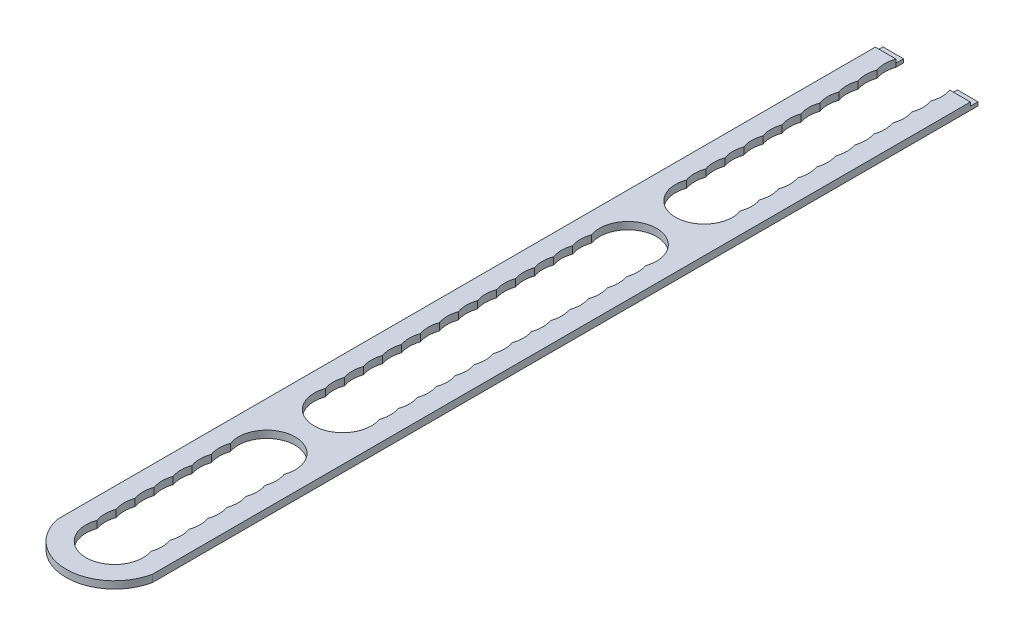
SolidWorks part; units mm, degrees
ref_plane "Front Plane" through (0, 0, 0) normal (0, 0, 1) x (1, 0, 0)
ref_plane "Top Plane" through (0, 0, 0) normal (0, 1, 0) x (1, 0, 0)
ref_plane "Right Plane" through (0, 0, 0) normal (1, 0, 0) x (0, 0, -1)
sketch "Sketch6" plane through (0, 0, 0) normal (0, 1, 0) x (1, 0, 0)
  line L0 (0, 195) -> (0, -195) construction
  line L1 (-12.5, -195) -> (12.5, -195)
  line L2 (-12.5, -195) -> (-12.5, 195)
  line L3 (-12.5, 195) -> (12.5, 195)
  line L4 (12.5, -195) -> (12.5, 195)
  line L5 (-12.5, -195) -> (12.5, 195) construction
  line L6 (-12.5, 195) -> (12.5, -195) construction
  line L7 (-12.5, 22.5) -> (12.5, 22.5)
  line L8 (-12.5, -46.875) -> (12.5, -46.875) construction
  line L9 (-12.5, -140.625) -> (12.5, -140.625) construction
  arc A0 (7.0711, 2.5) -> (7.0711, -2.5) centre (0, 0) cw
  arc A1 (7.0711, -2.5) -> (7.0711, -7.5) centre (0, -5) cw
  arc A2 (7.0711, -7.5) -> (7.0711, -12.5) centre (0, -10) cw
  arc A3 (7.0711, -12.5) -> (7.0711, -17.5) centre (0, -15) cw
  arc A4 (7.0711, -17.5) -> (7.0711, -22.5) centre (0, -20) cw
  arc A5 (7.0711, -22.5) -> (7.0711, -27.5) centre (0, -25) cw
  arc A6 (7.0711, -27.5) -> (7.0711, -32.5) centre (0, -30) cw
  arc A7 (7.0711, -32.5) -> (7.0711, -37.5) centre (0, -35) cw
  arc A8 (7.0711, -37.5) -> (7.0711, -42.5) centre (0, -40) cw
  arc A9 (7.0711, -42.5) -> (7.0711, -47.5) centre (0, -45) cw
  arc A10 (7.0711, -47.5) -> (7.0711, -52.5) centre (0, -50) cw
  arc A11 (7.0711, -52.5) -> (7.0711, -57.5) centre (0, -55) cw
  arc A12 (7.0711, -57.5) -> (7.0711, -62.5) centre (0, -60) cw
  arc A13 (7.0711, -62.5) -> (7.0711, -67.5) centre (0, -65) cw
  arc A14 (7.0711, -67.5) -> (7.0711, -72.5) centre (0, -70) cw
  arc A15 (7.0711, -72.5) -> (7.0711, -77.5) centre (0, -75) cw
  arc A16 (7.0711, -77.5) -> (7.0711, -82.5) centre (0, -80) cw
  arc A17 (7.0711, -82.5) -> (7.0711, -87.5) centre (0, -85) cw
  arc A18 (7.0711, -87.5) -> (7.0711, -92.5) centre (0, -90) cw
  arc A19 (7.0711, -92.5) -> (7.0711, -97.5) centre (0, -95) cw
  arc A20 (7.0711, -97.5) -> (7.0711, -102.5) centre (0, -100) cw
  arc A21 (7.0711, -102.5) -> (7.0711, -107.5) centre (0, -105) cw
  arc A22 (7.0711, -107.5) -> (7.0711, -112.5) centre (0, -110) cw
  arc A23 (7.0711, -112.5) -> (7.0711, -117.5) centre (0, -115) cw
  arc A24 (7.0711, -117.5) -> (7.0711, -122.5) centre (0, -120) cw
  arc A25 (7.0711, -122.5) -> (7.0711, -127.5) centre (0, -125) cw
  arc A26 (7.0711, -127.5) -> (7.0711, -132.5) centre (0, -130) cw
  arc A27 (7.0711, -132.5) -> (7.0711, -137.5) centre (0, -135) cw
  arc A28 (7.0711, -137.5) -> (7.0711, -142.5) centre (0, -140) cw
  arc A29 (7.0711, -142.5) -> (7.0711, -147.5) centre (0, -145) cw
  arc A30 (7.0711, -147.5) -> (7.0711, -152.5) centre (0, -150) cw
  arc A31 (7.0711, -152.5) -> (7.0711, -157.5) centre (0, -155) cw
  arc A32 (7.0711, -157.5) -> (7.0711, -162.5) centre (0, -160) cw
  arc A33 (7.0711, -162.5) -> (7.0711, -167.5) centre (0, -165) cw
  arc A34 (7.0711, -167.5) -> (7.0711, -172.5) centre (0, -170) cw
  arc A35 (7.0711, -172.5) -> (7.0711, -177.5) centre (0, -175) cw
  arc A36 (7.0711, -177.5) -> (7.0711, -182.5) centre (0, -180) cw
  arc A37 (7.0711, -182.5) -> (7.0711, -187.5) centre (0, -185) cw
  arc A38 (7.0711, -187.5) -> (7.0711, -192.5) centre (0, -190) cw
  arc A39 (-7.0711, -187.5) -> (-7.0711, -192.5) centre (0, -190) ccw
  arc A40 (-7.0711, -182.5) -> (-7.0711, -187.5) centre (0, -185) ccw
  arc A41 (-7.0711, -177.5) -> (-7.0711, -182.5) centre (0, -180) ccw
  arc A42 (-7.0711, -172.5) -> (-7.0711, -177.5) centre (0, -175) ccw
  arc A43 (-7.0711, -167.5) -> (-7.0711, -172.5) centre (0, -170) ccw
  arc A44 (-7.0711, -162.5) -> (-7.0711, -167.5) centre (0, -165) ccw
  arc A45 (-7.0711, -157.5) -> (-7.0711, -162.5) centre (0, -160) ccw
  arc A46 (-7.0711, -152.5) -> (-7.0711, -157.5) centre (0, -155) ccw
  arc A47 (-7.0711, -147.5) -> (-7.0711, -152.5) centre (0, -150) ccw
  arc A48 (-7.0711, -142.5) -> (-7.0711, -147.5) centre (0, -145) ccw
  arc A49 (-7.0711, -137.5) -> (-7.0711, -142.5) centre (0, -140) ccw
  arc A50 (-7.0711, -132.5) -> (-7.0711, -137.5) centre (0, -135) ccw
  arc A51 (-7.0711, -127.5) -> (-7.0711, -132.5) centre (0, -130) ccw
  arc A52 (-7.0711, -122.5) -> (-7.0711, -127.5) centre (0, -125) ccw
  arc A53 (-7.0711, -117.5) -> (-7.0711, -122.5) centre (0, -120) ccw
  arc A54 (-7.0711, -112.5) -> (-7.0711, -117.5) centre (0, -115) ccw
  arc A55 (-7.0711, -107.5) -> (-7.0711, -112.5) centre (0, -110) ccw
  arc A56 (-7.0711, -102.5) -> (-7.0711, -107.5) centre (0, -105) ccw
  arc A57 (-7.0711, -97.5) -> (-7.0711, -102.5) centre (0, -100) ccw
  arc A58 (-7.0711, -92.5) -> (-7.0711, -97.5) centre (0, -95) ccw
  arc A59 (-7.0711, -87.5) -> (-7.0711, -92.5) centre (0, -90) ccw
  arc A60 (-7.0711, -82.5) -> (-7.0711, -87.5) centre (0, -85) ccw
  arc A61 (-7.0711, -77.5) -> (-7.0711, -82.5) centre (0, -80) ccw
  arc A62 (-7.0711, -72.5) -> (-7.0711, -77.5) centre (0, -75) ccw
  arc A63 (-7.0711, -67.5) -> (-7.0711, -72.5) centre (0, -70) ccw
  arc A64 (-7.0711, -62.5) -> (-7.0711, -67.5) centre (0, -65) ccw
  arc A65 (-7.0711, -57.5) -> (-7.0711, -62.5) centre (0, -60) ccw
  arc A66 (-7.0711, -52.5) -> (-7.0711, -57.5) centre (0, -55) ccw
  arc A67 (-7.0711, -47.5) -> (-7.0711, -52.5) centre (0, -50) ccw
  arc A68 (-7.0711, -42.5) -> (-7.0711, -47.5) centre (0, -45) ccw
  arc A69 (-7.0711, -37.5) -> (-7.0711, -42.5) centre (0, -40) ccw
  arc A70 (-7.0711, -32.5) -> (-7.0711, -37.5) centre (0, -35) ccw
  arc A71 (-7.0711, -27.5) -> (-7.0711, -32.5) centre (0, -30) ccw
  arc A72 (-7.0711, -22.5) -> (-7.0711, -27.5) centre (0, -25) ccw
  arc A73 (-7.0711, -17.5) -> (-7.0711, -22.5) centre (0, -20) ccw
  arc A74 (-7.0711, -12.5) -> (-7.0711, -17.5) centre (0, -15) ccw
  arc A75 (-7.0711, -7.5) -> (-7.0711, -12.5) centre (0, -10) ccw
  arc A76 (-7.0711, -2.5) -> (-7.0711, -7.5) centre (0, -5) ccw
  arc A77 (-7.0711, 2.5) -> (-7.0711, -2.5) centre (0, 0) ccw
  arc A78 (-7.0711, -192.5) -> (7.0711, -192.5) centre (0, -190) ccw
  arc A79 (-12.5, -192.5) -> (12.5, -192.5) centre (0, -190) ccw
  arc A80 (-7.0711, -37.5) -> (7.0711, -37.5) centre (0, -35) ccw
  arc A81 (-7.0711, -52.5) -> (7.0711, -52.5) centre (0, -55) cw
  arc A82 (-7.0711, -132.5) -> (7.0711, -132.5) centre (0, -130) ccw
  arc A83 (-7.0711, -147.5) -> (7.0711, -147.5) centre (0, -150) cw
  arc A84 (7.0711, 7.5) -> (7.0711, 2.5) centre (0, 5) cw
  arc A85 (7.0711, 12.5) -> (7.0711, 7.5) centre (0, 10) cw
  arc A86 (7.0711, 17.5) -> (7.0711, 12.5) centre (0, 15) cw
  arc A87 (7.0711, 22.5) -> (7.0711, 17.5) centre (0, 20) cw
  arc A88 (-7.0711, 22.5) -> (-7.0711, 17.5) centre (0, 20) ccw
  arc A89 (-7.0711, 17.5) -> (-7.0711, 12.5) centre (0, 15) ccw
  arc A90 (-7.0711, 12.5) -> (-7.0711, 7.5) centre (0, 10) ccw
  arc A91 (-7.0711, 7.5) -> (-7.0711, 2.5) centre (0, 5) ccw
  point P0 (0, 0)
  dimension "D4" = 7.5
  dimension "D1" = 25
  dimension "D2" = 390
  dimension "D3" = 5
  dimension "D6" = 46.875
  dimension "D7" = 93.75
  dimension "D5" = 39
  dimension "D8" = 5
extrude "Boss-Extrude4" add sketch "Sketch6" along normal blind 1.9
sketch "Sketch7" plane through (0, 0, 0) normal (0, 1, 0) x (1, 0, 0)
  line L1 (-12.5, 22.5) -> (-7.0711, 22.5)
  line L2 (-12.5, 22.5) -> (-12.5, 24.5)
  line L3 (-12.5, 24.5) -> (-7.0711, 24.5)
  line L4 (-7.0711, 22.5) -> (-7.0711, 24.5)
  line L5 (7.0711, 22.5) -> (12.5, 22.5)
  line L6 (7.0711, 22.5) -> (7.0711, 24.5)
  line L7 (7.0711, 24.5) -> (12.5, 24.5)
  line L8 (12.5, 22.5) -> (12.5, 24.5)
  line L9 (12.5, -192.5) -> (12.5, 22.5) construction
  point P5 (0, 0)
  point P13 (0, 0)
  point P14 (0, 0)
  point P15 (0, 0)
  point P17 (0, 0)
  point P19 (0, 0)
  point P21 (0, 0)
  dimension "D1" = 2
extrude "Boss-Extrude5" add sketch "Sketch7" along normal blind 0.95 contours L1 L4 L3 L2 | L5 L8 L7 L6
equation "\"diameter_electrode_outer\"= 15mm"
equation "\"width_wing\"= 5mm"
equation "\"rad_curve\"= \"diameter_electrode_outer\" / 2"
equation "\"length_wing\"= 10mm"
equation "\"range_electrode_move_horizontal\"= ( \"length_wing\" / 2 ) * 66"
equation "\"length_slit_horizontal\"= \"diameter_electrode_outer\" + \"range_electrode_move_horizontal\""
equation "\"width_frame\"= \"diameter_electrode_outer\" + \"width_wing\" * 2"
equation "\"height_frame\" = 1.9mm"
equation "\"diameter_fluid_tank_outer\" = 60mm"
equation "\"width_frame_support\"= 10mm"
equation "\"D1@Fillet2\"=\"rad_curve\""
equation "\"range_electrode_move_vertical\" = ( \"length_wing\" / 2 ) * 75"
equation "\"length_slit_vertical\"= \"diameter_electrode_outer\" + \"range_electrode_move_vertical\""
equation "\"circumference_head\"= 600mm"
equation "\"range_electrode_move_front\" = \"circumference_head\" * 3.5 / 10"
equation "\"length_slit_front\"= \"range_electrode_move_front\" + \"diameter_electrode_outer\""
equation "\"width_connect\"= 2mm"
equation "\"height_connect\"= \"height_frame\" / 2"
equation "\"D1@Sketch6\"=\"diameter_electrode_outer\"+\"width_wing\"*2"
equation "\"D2@Sketch6\"=\"length_slit_vertical\""
equation "\"D3@Sketch6\"=\"length_wing\"/2"
equation "\"D4@Sketch6\"=\"rad_curve\""
equation "\"D6@Sketch6\"=\"range_electrode_move_vertical\"/8"
equation "\"D7@Sketch6\"=\"range_electrode_move_vertical\"/4"
equation "\"D1@Sketch7\"=\"width_connect\""
equation "\"D1@Boss-Extrude5\"=\"height_connect\""
equation "\"D1@Boss-Extrude4\"=\"height_frame\""
equation "\"length_slit_vertical\"= \"range_electrode_move_vertical\" + \"diameter_electrode_outer\""
